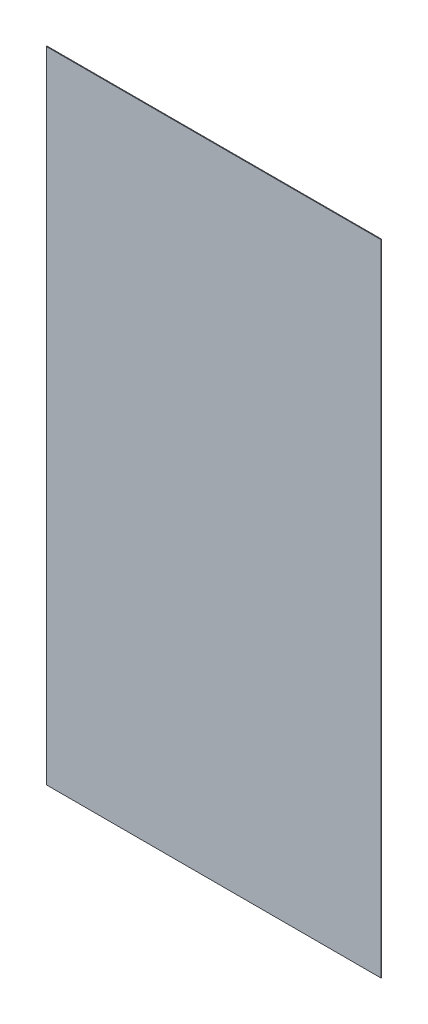
SolidWorks part; units mm, degrees
ref_plane "前视基准面" through (0, 0, 0) normal (0, 0, 1) x (1, 0, 0)
ref_plane "上视基准面" through (0, 0, 0) normal (0, 1, 0) x (1, 0, 0)
ref_plane "右视基准面" through (0, 0, 0) normal (1, 0, 0) x (0, 0, -1)
sketch "草图2" plane through (0, 0, 0) normal (0, 0, 1) x (1, 0, 0)
  line L1 (0, 0) -> (450, 0)
  line L2 (0, 0) -> (0, 860)
  line L3 (0, 860) -> (450, 860)
  line L4 (450, 0) -> (450, 860)
  dimension "D1" = 450
  dimension "D2" = 860
extrude "凸台-拉伸1" add sketch "草图2" along normal blind 1
